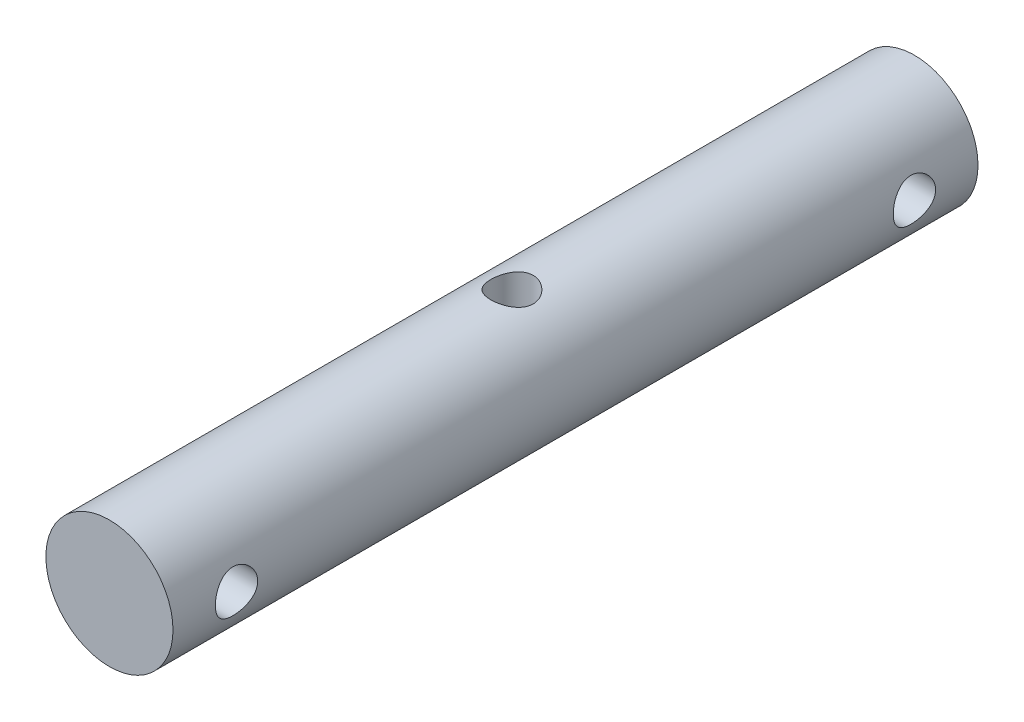
SolidWorks part; units mm, degrees
ref_plane "Front Plane" through (0, 0, 0) normal (0, 0, 1) x (1, 0, 0)
ref_plane "Top Plane" through (0, 0, 0) normal (0, 1, 0) x (1, 0, 0)
ref_plane "Right Plane" through (0, 0, 0) normal (1, 0, 0) x (0, 0, -1)
sketch "Sketch1" plane through (0, 0, 0) normal (0, 0, 1) x (1, 0, 0)
  circle A0 centre (0, 0) radius 3
  dimension "D1" = 6
extrude "Boss-Extrude1" add sketch "Sketch1" along normal blind 38
sketch "Sketch2" plane through (0, 0, 0) normal (0, 1, 0) x (1, 0, 0)
  circle A0 centre (0, -19) radius 1
  dimension "D1" = 2
extrude "Cut-Extrude3" cut sketch "Sketch2" against normal mid plane 38
sketch "Sketch4" plane through (0, 0, 0) normal (1, 0, 0) x (0, 0, -1)
  circle A0 centre (-35, 0) radius 1
  circle A1 centre (-3, 0) radius 1
extrude "Cut-Extrude4" cut sketch "Sketch4" against normal mid plane 38
